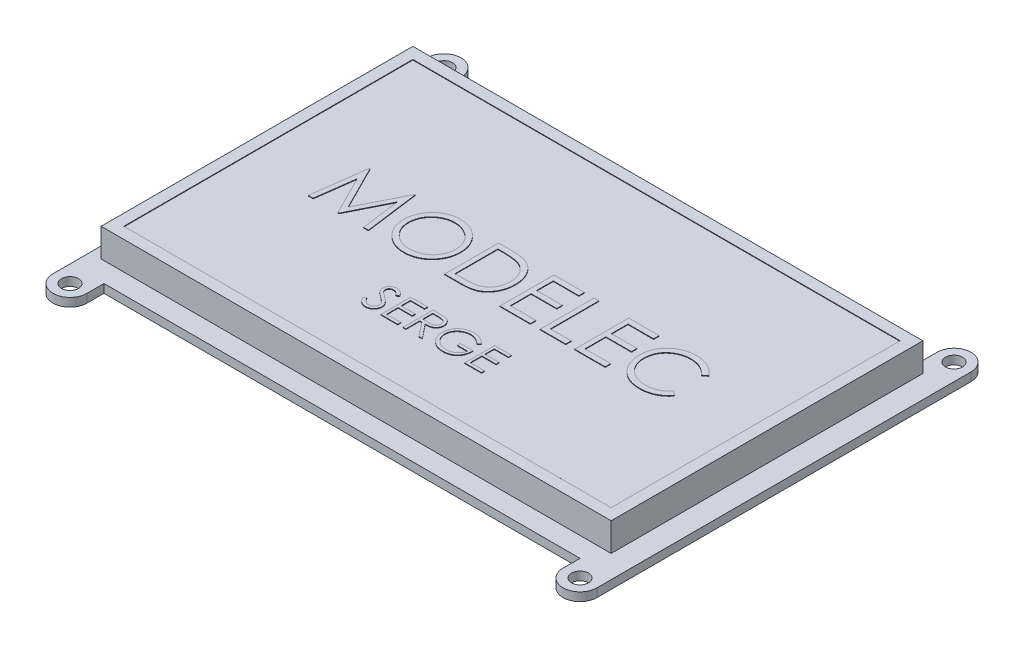
SolidWorks part; units mm, degrees
ref_plane "Plan de face" through (0, 0, 0) normal (0, 0, 1) x (1, 0, 0)
ref_plane "Plan de dessus" through (0, 0, 0) normal (0, 1, 0) x (1, 0, 0)
ref_plane "Plan de droite" through (0, 0, 0) normal (1, 0, 0) x (0, 0, -1)
sketch "Esquisse2" plane through (0, 0, 0) normal (0, 1, 0) x (1, 0, 0)
  line L0 (0, 67.1962) -> (0, -69.6908) construction
  line L1 (48, -30) -> (-48, -30) construction
  line L2 (48, -30) -> (48, 30) construction
  line L3 (48, 30) -> (-48, 30) construction
  line L4 (-48, -30) -> (-48, 30) construction
  line L5 (48, -30) -> (-48, 30) construction
  line L6 (48, 30) -> (-48, -30) construction
  line L7 (-48, 33) -> (-48, 30)
  line L8 (-42, 33) -> (-42, 30)
  line L10 (-48, 30) -> (-48, -30)
  line L11 (-42, 30) -> (42, 30)
  line L12 (48, 33) -> (48, 30)
  line L13 (42, 33) -> (42, 30)
  line L15 (48, 30) -> (48, -30)
  line L16 (-55, 0) -> (55, 0) construction
  line L17 (-42, -33) -> (-42, -30)
  line L18 (42, -33) -> (42, -30)
  line L19 (48, -33) -> (48, -30)
  line L21 (-42, -30) -> (42, -30)
  line L22 (-48, -33) -> (-48, -30)
  circle A0 centre (-45, 33) radius 1.5
  circle A1 centre (-45, 33) radius 3 construction
  arc A2 (-48, 33) -> (-42, 33) centre (-45, 33) cw
  circle A3 centre (45, 33) radius 1.5
  arc A4 (48, 33) -> (42, 33) centre (45, 33) ccw
  circle A5 centre (45, -33) radius 1.5
  arc A6 (48, -33) -> (42, -33) centre (45, -33) cw
  circle A7 centre (-45, -33) radius 1.5
  arc A8 (-48, -33) -> (-42, -33) centre (-45, -33) ccw
  point P0 (0, 0)
  point P15 (0, 0)
  point P17 (-48.7877, -30)
  point P24 (0, 30)
  point P35 (48, 0)
  point P39 (-48, 0)
  dimension "D1" = 90
  dimension "D4" = 3
  dimension "D5" = 3
  dimension "D3" = 3
  dimension "D6" = 60
extrude "Boss.-Extru.1" add sketch "Esquisse2" along normal blind 1.5
sketch "Esquisse3" plane through (0, 1.5, 0) normal (0, 1, 0) x (1, 0, 0)
  line L1 (42.5, -25) -> (-42.5, -25)
  line L2 (42.5, -25) -> (42.5, 25)
  line L3 (42.5, 25) -> (-42.5, 25)
  line L4 (-42.5, -25) -> (-42.5, 25)
  line L5 (42.5, -25) -> (-42.5, 25) construction
  line L6 (42.5, 25) -> (-42.5, -25) construction
  line L16 (-48, 33) -> (-48, -33)
  line L17 (-42, -33) -> (-42, -30)
  line L18 (-42, -30) -> (42, -30)
  line L19 (42, -30) -> (42, -33)
  line L20 (48, -33) -> (48, 33)
  line L25 (42, 33) -> (42, 30)
  line L26 (42, 30) -> (-42, 30)
  line L27 (-42, 30) -> (-42, 33)
  line L32 (-48, 33) -> (-48, -33)
  line L33 (-42, -33) -> (-42, -30)
  line L34 (-42, -30) -> (42, -30)
  line L35 (42, -30) -> (42, -33)
  line L36 (48, -33) -> (48, 33)
  line L41 (42, 33) -> (42, 30)
  line L42 (42, 30) -> (-42, 30)
  line L43 (-42, 30) -> (-42, 33)
  arc A4 (-48, -33) -> (-42, -33) centre (-45, -33) ccw
  arc A5 (42, -33) -> (48, -33) centre (45, -33) ccw
  arc A6 (48, 33) -> (42, 33) centre (45, 33) ccw
  arc A7 (-42, 33) -> (-48, 33) centre (-45, 33) ccw
  arc A8 (-48, -33) -> (-42, -33) centre (-45, -33) ccw
  arc A9 (42, -33) -> (48, -33) centre (45, -33) ccw
  arc A10 (48, 33) -> (42, 33) centre (45, 33) ccw
  arc A11 (-42, 33) -> (-48, 33) centre (-45, 33) ccw
  point P2 (0, 0)
  dimension "D2" = 85
  dimension "D3" = 50
  dimension "D1" = 0
extrude "Boss.-Extru.2" add sketch "Esquisse3" along normal blind 1 separate body contours L4 L1 L2 L3
sketch "Esquisse4" plane through (0, 2.5, 0) normal (0, 1, 0) x (1, 0, 0)
  line L1 (45, -27.5) -> (-45, -27.5)
  line L2 (45, -27.5) -> (45, 27.5)
  line L3 (45, 27.5) -> (-45, 27.5)
  line L4 (-45, -27.5) -> (-45, 27.5)
  line L5 (45, -27.5) -> (-45, 27.5) construction
  line L6 (45, 27.5) -> (-45, -27.5) construction
  point P0 (0, 0)
  dimension "D1" = 90
  dimension "D2" = 55
extrude "Boss.-Extru.3" add sketch "Esquisse4" along normal blind 5
sketch "Esquisse5" plane through (0, 7.5, 0) normal (0, 1, 0) x (1, 0, 0)
  line L0 (-45, 27.5) -> (-45, -27.5) construction
  line L1 (43, -25.5) -> (-43, -25.5)
  line L2 (43, -25.5) -> (43, 25.5)
  line L3 (43, 25.5) -> (-43, 25.5)
  line L4 (-43, -25.5) -> (-43, 25.5)
  line L5 (43, -25.5) -> (-43, 25.5) construction
  line L6 (43, 25.5) -> (-43, -25.5) construction
  line L7 (45, 27.5) -> (-45, 27.5) construction
  point P0 (0, 0)
  dimension "D1" = 2
  dimension "D2" = 2
extrude "Enlèv. mat.-Extru.1" cut sketch "Esquisse5" against normal blind 0.1
sketch "Esquisse6" plane through (0, 7.4, 0) normal (0, 1, 0) x (1, 0, 0)
  line L0 (-43, -4.5) -> (43, -4.5) construction
  line L3 (43, 25.5) -> (-43, 25.5) construction
  line L4 (-43, -16.2982) -> (43, -16.2982) construction
  line L5 (-43, 25.5) -> (-43, -25.5) construction
  line L6 (43, -25.5) -> (43, 25.5) construction
  text T0 "MODELEC" font "Century Gothic" height in points 36
  text T1 "SERGE" font "Century Gothic" height in points 20
  dimension "D1" = 30
extrude "Boss.-Extru.4" add sketch "Esquisse6" along normal blind 0.1
